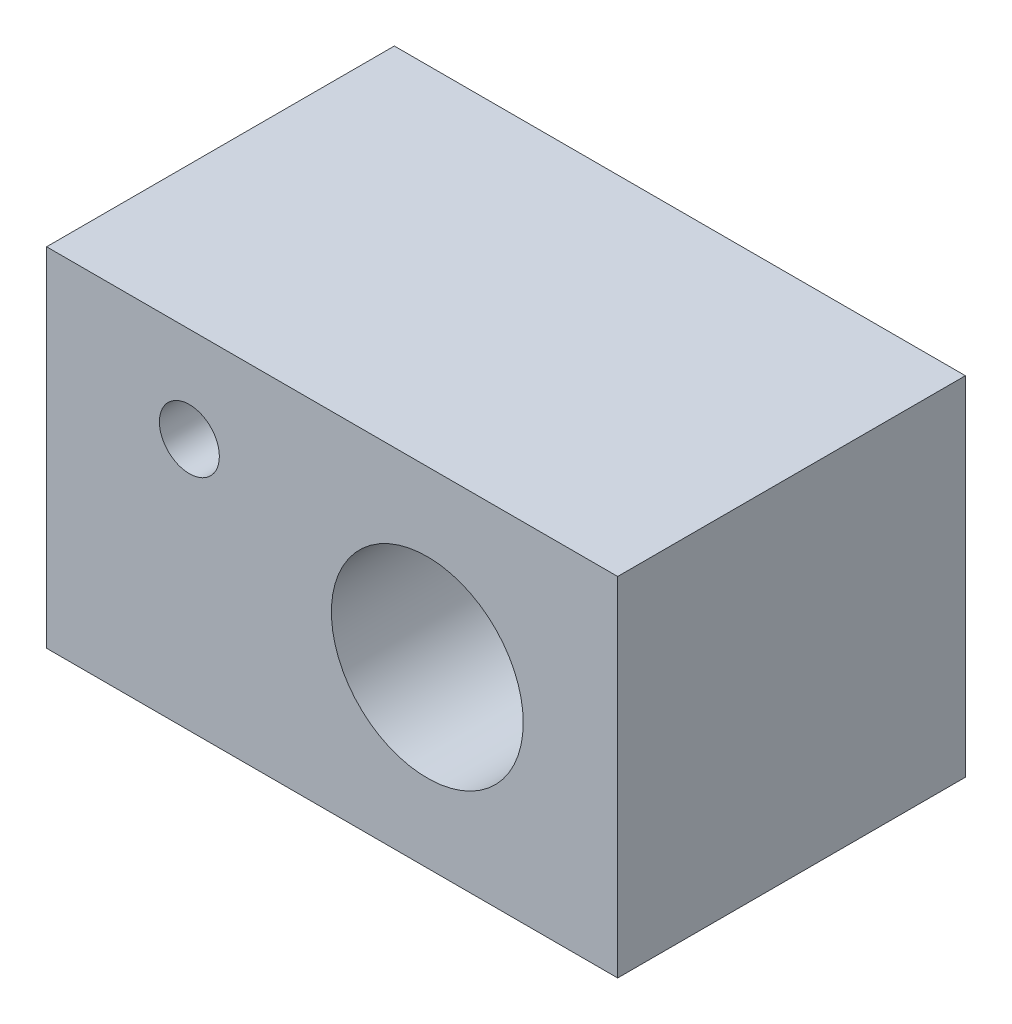
SolidWorks part; units mm, degrees
ref_plane "Front Plane" through (0, 0, 0) normal (0, 0, 1) x (1, 0, 0)
ref_plane "Top Plane" through (0, 0, 0) normal (0, 1, 0) x (1, 0, 0)
ref_plane "Right Plane" through (0, 0, 0) normal (1, 0, 0) x (0, 0, -1)
sketch "Sketch1" plane through (0, 0, 0) normal (0, 0, 1) x (1, 0, 0)
  line L1 (0, 0) -> (9.525, 0)
  line L2 (0, 0) -> (0, 5.8)
  line L3 (0, 5.8) -> (9.525, 5.8)
  line L4 (9.525, 0) -> (9.525, 5.8)
  dimension "D1" = 9.525
  dimension "D2" = 5.8
extrude "Boss-Extrude1" add sketch "Sketch1" along normal blind 5.8
hole_wizard "M3 Clearance Hole1" positions "Sketch4" profile "Sketch3" hole size "M3" standard "Ansi Metric"
sketch "Sketch4" plane through (0, 0, 5.8) normal (0, 0, 1) x (1, 0, 0)
  line L0 (6.35, 2.9) -> (9.525, 2.9) construction
  line L1 (9.525, 0) -> (9.525, 5.8) construction
  point P0 (6.35, 2.9)
  dimension "D1" = 3.175
sketch "Sketch3" plane through (6.35, 2.9, 5.8) normal (1, 0, 0) x (0, -1, 0)
  line L0 (0, 0) -> (0, 13.6614)
  line L1 (0, 13.6614) -> (1.6, 12.7)
  line L2 (1.6, 12.7) -> (1.6, 0)
  line L5 (1.6, 0) -> (0, 0)
  line L10 (0, 13.6614) -> (-1.6, 12.7) construction
  line L11 (0, -6.35) -> (0, 107.95) construction
  dimension "Hole Dia." = 3.2
  dimension "Hole Depth" = 12.7
  dimension "Drill Angle" = 118
sketch "Sketch5" plane through (0, 0, 5.8) normal (0, 0, 1) x (1, 0, 0)
  line L0 (0, 5.8) -> (0, 0) construction
  line L1 (9.525, 5.8) -> (0, 5.8) construction
  circle A0 centre (2.3813, 4.2125) radius 0.5
  dimension "D2" = 1
  dimension "D1" = 2.3813
  dimension "D3" = 1.5875
extrude "Cut-Extrude1" cut sketch "Sketch5" against normal blind 5.8
